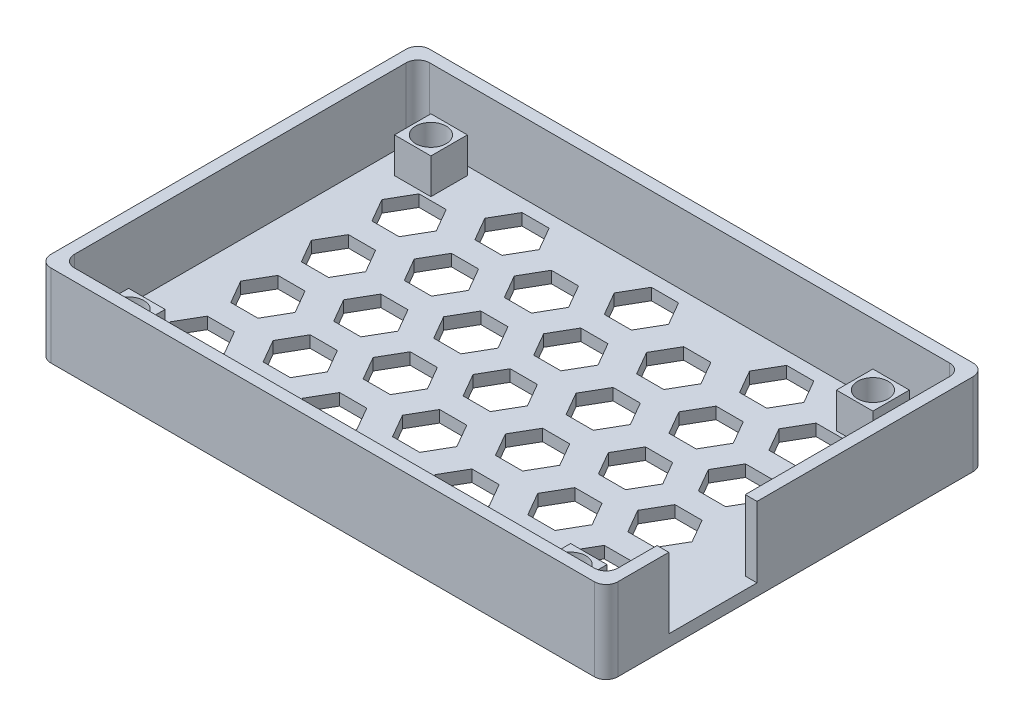
SolidWorks part; units mm, degrees
ref_plane "Plan de face" through (0, 0, 0) normal (0, 0, 1) x (1, 0, 0)
ref_plane "Plan de dessus" through (0, 0, 0) normal (0, 1, 0) x (1, 0, 0)
ref_plane "Plan de droite" through (0, 0, 0) normal (1, 0, 0) x (0, 0, -1)
sketch "Esquisse1" plane through (0, 0, 0) normal (0, 1, 0) x (1, 0, 0)
  line L1 (-48.6494, -29.5203) -> (47.3506, -29.5203)
  line L2 (-48.6494, -29.5203) -> (-48.6494, 34.4797)
  line L3 (-48.6494, 34.4797) -> (47.3506, 34.4797)
  line L4 (47.3506, -29.5203) -> (47.3506, 34.4797)
  dimension "D1" = 64
  dimension "D2" = 96
extrude "Boss.-Extru.1" add sketch "Esquisse1" along normal blind 14
sketch "Esquisse2" plane through (0, 14, 0) normal (0, 1, 0) x (1, 0, 0)
  line L0 (-48.6494, 34.4797) -> (-48.6494, -29.5203) construction
  line L1 (-46.6494, 32.4797) -> (45.3506, 32.4797)
  line L2 (-46.6494, 32.4797) -> (-46.6494, -27.5203)
  line L3 (-46.6494, -27.5203) -> (45.3506, -27.5203)
  line L4 (45.3506, 32.4797) -> (45.3506, -27.5203)
  line L5 (47.3506, 34.4797) -> (-48.6494, 34.4797) construction
  dimension "D1" = 2
  dimension "D2" = 92
  dimension "D3" = 2
  dimension "D4" = 60
extrude "Enlèv. mat.-Extru.1" cut sketch "Esquisse2" against normal blind 10.8
sketch "Esquisse3" plane through (0, 3.2, 0) normal (0, 1, 0) x (1, 0, 0)
  line L0 (45.3506, 32.4797) -> (-46.6494, 32.4797) construction
  line L1 (-37.6494, 32.4797) -> (30.3506, 32.4797)
  line L2 (-37.6494, 32.4797) -> (-37.6494, -27.5203)
  line L3 (-37.6494, -27.5203) -> (30.3506, -27.5203)
  line L4 (30.3506, 32.4797) -> (30.3506, -27.5203)
  line L5 (-46.6494, -27.5203) -> (45.3506, -27.5203) construction
  line L6 (-46.6494, 32.4797) -> (-46.6494, -27.5203) construction
  line L7 (45.3506, -27.5203) -> (45.3506, 32.4797) construction
  dimension "D1" = 9
  dimension "D2" = 15
extrude "Enlèv. mat.-Extru.2" cut sketch "Esquisse3" against normal blind 1.2
sketch "Esquisse4" plane through (0, 3.2, 0) normal (0, 1, 0) x (1, 0, 0)
  line L0 (-46.6494, 32.4797) -> (-46.6494, -27.5203) construction
  line L1 (-46.6494, 25.4797) -> (45.3506, 25.4797)
  line L2 (-46.6494, 25.4797) -> (-46.6494, -20.5203)
  line L3 (-46.6494, -20.5203) -> (45.3506, -20.5203)
  line L4 (45.3506, 25.4797) -> (45.3506, -20.5203)
  line L5 (45.3506, -27.5203) -> (45.3506, 32.4797) construction
  line L6 (-37.6494, 32.4797) -> (-46.6494, 32.4797) construction
  line L7 (-37.6494, -27.5203) -> (30.3506, -27.5203) construction
  dimension "D1" = 7
  dimension "D2" = 7
extrude "Enlèv. mat.-Extru.3" cut sketch "Esquisse4" against normal blind 1.2
sketch "Esquisse6" plane through (0, 3.2, 0) normal (0, 1, 0) x (1, 0, 0)
  line L0 (45.3506, 25.4797) -> (45.3506, 32.4797) construction
  line L1 (45.3506, -27.5203) -> (45.3506, -20.5203) construction
  line L2 (45.3506, 32.4797) -> (30.3506, 32.4797) construction
  line L4 (-37.6494, 32.4797) -> (-46.6494, 32.4797) construction
  circle A0 centre (-40.1294, 28.1747) radius 1.15
  circle A1 centre (-40.1294, -23.2153) radius 1.15
  circle A2 centre (35.0106, 28.1747) radius 1.15
  circle A3 centre (35.0106, -23.2153) radius 1.15
  dimension "D1" = 51.39
  dimension "D2" = 51.39
  dimension "D3" = 10.34
  dimension "D4" = 10.34
  dimension "D5" = 4.305
  dimension "D6" = 75.14
  dimension "D7" = 75.14
  dimension "D8" = 4.305
extrude "Boss.-Extru.2" add sketch "Esquisse6" along normal blind 4.8
sketch "Esquisse7" plane through (0, 3.2, 0) normal (0, 1, 0) x (1, 0, 0)
  line L1 (-42.2794, 30.3247) -> (-37.9794, 30.3247)
  line L2 (-42.2794, 30.3247) -> (-42.2794, 26.0247)
  line L3 (-42.2794, 26.0247) -> (-37.9794, 26.0247)
  line L4 (-37.9794, 30.3247) -> (-37.9794, 26.0247)
  line L5 (-42.2794, -25.3653) -> (-37.9794, -25.3653)
  line L6 (-42.2794, -25.3653) -> (-42.2794, -21.0653)
  line L7 (-42.2794, -21.0653) -> (-37.9794, -21.0653)
  line L8 (-37.9794, -25.3653) -> (-37.9794, -21.0653)
  line L9 (32.8606, 30.3247) -> (37.1606, 30.3247)
  line L10 (32.8606, 30.3247) -> (32.8606, 26.0247)
  line L11 (32.8606, 26.0247) -> (37.1606, 26.0247)
  line L12 (37.1606, 30.3247) -> (37.1606, 26.0247)
  line L13 (32.8606, -21.0653) -> (37.1606, -21.0653)
  line L14 (32.8606, -21.0653) -> (32.8606, -25.3653)
  line L15 (32.8606, -25.3653) -> (37.1606, -25.3653)
  line L16 (37.1606, -21.0653) -> (37.1606, -25.3653)
  circle A0 centre (-40.1294, 28.1747) radius 1.15
  circle A1 centre (-40.1294, -23.2153) radius 1.15
  circle A2 centre (35.0106, 28.1747) radius 1.15
  circle A3 centre (35.0106, -23.2153) radius 1.15
  dimension "D1" = 4.3
  dimension "D2" = 4.3
  dimension "D3" = 2.15
  dimension "D4" = 2.15
  dimension "D5" = 4.3
  dimension "D6" = 4.3
  dimension "D7" = 2.15
  dimension "D8" = 2.15
  dimension "D9" = 4.3
  dimension "D10" = 4.3
  dimension "D11" = 2.15
  dimension "D12" = 2.15
  dimension "D13" = 4.3
  dimension "D14" = 4.3
  dimension "D15" = 2.15
  dimension "D16" = 2.15
extrude "Boss.-Extru.3" add sketch "Esquisse7" along normal blind 4.8
sketch "Esquisse8" plane through (0, 8, 0) normal (0, 1, 0) x (1, 0, 0)
  line L0 (-37.9794, 30.3247) -> (-42.2794, 30.3247) construction
  line L1 (-42.2794, 30.3247) -> (-42.2794, 26.0247) construction
  line L2 (-42.2794, -21.0653) -> (-42.2794, -25.3653) construction
  line L3 (-37.9794, -21.0653) -> (-42.2794, -21.0653) construction
  line L4 (37.1606, -25.3653) -> (37.1606, -21.0653) construction
  line L5 (37.1606, -21.0653) -> (32.8606, -21.0653) construction
  line L6 (37.1606, 30.3247) -> (32.8606, 30.3247) construction
  line L7 (37.1606, 26.0247) -> (37.1606, 30.3247) construction
  circle A0 centre (-40.1294, -23.2153) radius 1.2
  circle A1 centre (-40.1294, 28.1747) radius 1.2
  circle A2 centre (35.0106, 28.1747) radius 1.2
  circle A3 centre (35.0106, -23.2153) radius 1.2
  dimension "D1" = 2.15
  dimension "D2" = 2.15
  dimension "D3" = 2.15
  dimension "D4" = 2.15
  dimension "D5" = 2.15
  dimension "D6" = 2.15
  dimension "D7" = 2.15
  dimension "D8" = 2.15
extrude "Enlèv. mat.-Extru.4" cut sketch "Esquisse8" against normal blind 4.8
sketch "Esquisse10" plane through (0, 3.2, 0) normal (0, 1, 0) x (1, 0, 0)
  line L1 (-46.6494, 32.4797) -> (45.3506, 32.4797)
  line L2 (-46.6494, 32.4797) -> (-46.6494, -27.5203)
  line L3 (-46.6494, -27.5203) -> (45.3506, -27.5203)
  line L4 (45.3506, 32.4797) -> (45.3506, -27.5203)
extrude "Enlèv. mat.-Extru.5" cut sketch "Esquisse10" against normal blind 1.2
sketch "Esquisse11" plane through (0, 2, 0) normal (0, 1, 0) x (1, 0, 0)
  line L1 (-42.2794, 30.3247) -> (-37.9794, 30.3247)
  line L2 (-42.2794, 30.3247) -> (-42.2794, 26.0247)
  line L3 (-42.2794, 26.0247) -> (-37.9794, 26.0247)
  line L4 (-37.9794, 30.3247) -> (-37.9794, 26.0247)
extrude "Boss.-Extru.4" add sketch "Esquisse11" along normal blind 1.2
sketch "Esquisse12" plane through (0, 2, 0) normal (0, 1, 0) x (1, 0, 0)
  line L1 (-42.2794, -21.0653) -> (-37.9794, -21.0653)
  line L2 (-42.2794, -21.0653) -> (-42.2794, -25.3653)
  line L3 (-42.2794, -25.3653) -> (-37.9794, -25.3653)
  line L4 (-37.9794, -21.0653) -> (-37.9794, -25.3653)
extrude "Boss.-Extru.5" add sketch "Esquisse12" along normal blind 1.2
sketch "Esquisse15" plane through (0, 2, 0) normal (0, 1, 0) x (1, 0, 0)
  line L1 (32.8606, 30.3247) -> (37.1606, 30.3247)
  line L2 (32.8606, 30.3247) -> (32.8606, 26.0247)
  line L3 (32.8606, 26.0247) -> (37.1606, 26.0247)
  line L4 (37.1606, 30.3247) -> (37.1606, 26.0247)
extrude "Boss.-Extru.8" add sketch "Esquisse15" along normal blind 1.2
sketch "Esquisse16" plane through (0, 2, 0) normal (0, 1, 0) x (1, 0, 0)
  line L1 (32.8606, -25.3653) -> (37.1606, -25.3653)
  line L2 (32.8606, -25.3653) -> (32.8606, -21.0653)
  line L3 (32.8606, -21.0653) -> (37.1606, -21.0653)
  line L4 (37.1606, -25.3653) -> (37.1606, -21.0653)
extrude "Boss.-Extru.9" add sketch "Esquisse16" along normal blind 1.2
sketch "Esquisse20" plane through (45.3506, 0, 0) normal (-1, 0, 0) x (0, 0, 1)
  line L0 (27.5203, 2) -> (-32.4797, 2) construction
  line L1 (19.0653, 2) -> (9.0653, 2)
  line L2 (19.0653, 2) -> (19.0653, 14)
  line L3 (19.0653, 14) -> (9.0653, 14)
  line L4 (9.0653, 2) -> (9.0653, 14)
  line L5 (21.0653, 8) -> (21.0653, 2) construction
  dimension "D1" = 2
  dimension "D2" = 10
  dimension "D3" = 12
extrude "Enlèv. mat.-Extru.8" cut sketch "Esquisse20" against normal blind 4.2
sketch "Esquisse22" plane through (0, 2, 0) normal (0, 1, 0) x (1, 0, 0)
  line L0 (45.3506, 32.4797) -> (-46.6494, 32.4797) construction
  line L1 (1.9694, 2.4797) -> (-0.34, 6.4797)
  line L2 (-0.34, 6.4797) -> (-4.9588, 6.4797)
  line L3 (-4.9588, 6.4797) -> (-7.2682, 2.4797)
  line L4 (-7.2682, 2.4797) -> (-4.9588, -1.5203)
  line L5 (-4.9588, -1.5203) -> (-0.34, -1.5203)
  line L6 (-0.34, -1.5203) -> (1.9694, 2.4797)
  line L8 (-46.6494, 32.4797) -> (-46.6494, -27.5203) construction
  line L9 (24.9694, 2.4797) -> (22.66, 6.4797)
  line L10 (22.66, 6.4797) -> (18.0412, 6.4797)
  line L11 (18.0412, 6.4797) -> (15.7318, 2.4797)
  line L12 (15.7318, 2.4797) -> (18.0412, -1.5203)
  line L13 (18.0412, -1.5203) -> (22.66, -1.5203)
  line L14 (22.66, -1.5203) -> (24.9694, 2.4797)
  line L15 (24.9694, 14.4797) -> (22.66, 18.4797)
  line L16 (22.66, 18.4797) -> (18.0412, 18.4797)
  line L17 (18.0412, 18.4797) -> (15.7318, 14.4797)
  line L18 (15.7318, 14.4797) -> (18.0412, 10.4797)
  line L19 (18.0412, 10.4797) -> (22.66, 10.4797)
  line L20 (22.66, 10.4797) -> (24.9694, 14.4797)
  line L21 (24.9694, 26.4797) -> (22.66, 30.4797)
  line L22 (22.66, 30.4797) -> (18.0412, 30.4797)
  line L23 (18.0412, 30.4797) -> (15.7318, 26.4797)
  line L24 (15.7318, 26.4797) -> (18.0412, 22.4797)
  line L25 (18.0412, 22.4797) -> (22.66, 22.4797)
  line L26 (22.66, 22.4797) -> (24.9694, 26.4797)
  line L27 (1.9694, 14.4797) -> (-0.34, 18.4797)
  line L28 (-0.34, 18.4797) -> (-4.9588, 18.4797)
  line L29 (-4.9588, 18.4797) -> (-7.2682, 14.4797)
  line L30 (-7.2682, 14.4797) -> (-4.9588, 10.4797)
  line L31 (-4.9588, 10.4797) -> (-0.34, 10.4797)
  line L32 (-0.34, 10.4797) -> (1.9694, 14.4797)
  line L33 (1.9694, 26.4797) -> (-0.34, 30.4797)
  line L34 (-0.34, 30.4797) -> (-4.9588, 30.4797)
  line L35 (-4.9588, 30.4797) -> (-7.2682, 26.4797)
  line L36 (-7.2682, 26.4797) -> (-4.9588, 22.4797)
  line L37 (-4.9588, 22.4797) -> (-0.34, 22.4797)
  line L38 (-0.34, 22.4797) -> (1.9694, 26.4797)
  line L39 (1.9694, -9.5203) -> (-0.34, -5.5203)
  line L40 (-0.34, -5.5203) -> (-4.9588, -5.5203)
  line L41 (-4.9588, -5.5203) -> (-7.2682, -9.5203)
  line L42 (-7.2682, -9.5203) -> (-4.9588, -13.5203)
  line L43 (-4.9588, -13.5203) -> (-0.34, -13.5203)
  line L44 (-0.34, -13.5203) -> (1.9694, -9.5203)
  line L45 (24.9694, -9.5203) -> (22.66, -5.5203)
  line L46 (22.66, -5.5203) -> (18.0412, -5.5203)
  line L47 (18.0412, -5.5203) -> (15.7318, -9.5203)
  line L48 (15.7318, -9.5203) -> (18.0412, -13.5203)
  line L49 (18.0412, -13.5203) -> (22.66, -13.5203)
  line L50 (22.66, -13.5203) -> (24.9694, -9.5203)
  line L51 (1.9694, -21.5203) -> (-0.34, -17.5203)
  line L52 (-0.34, -17.5203) -> (-4.9588, -17.5203)
  line L53 (-4.9588, -17.5203) -> (-7.2682, -21.5203)
  line L54 (-7.2682, -21.5203) -> (-4.9588, -25.5203)
  line L55 (-4.9588, -25.5203) -> (-0.34, -25.5203)
  line L56 (-0.34, -25.5203) -> (1.9694, -21.5203)
  line L57 (24.9694, -21.5203) -> (22.66, -17.5203)
  line L58 (22.66, -17.5203) -> (18.0412, -17.5203)
  line L59 (18.0412, -17.5203) -> (15.7318, -21.5203)
  line L60 (15.7318, -21.5203) -> (18.0412, -25.5203)
  line L61 (18.0412, -25.5203) -> (22.66, -25.5203)
  line L62 (22.66, -25.5203) -> (24.9694, -21.5203)
  line L63 (-20.0306, 26.4797) -> (-22.34, 30.4797)
  line L64 (-22.34, 30.4797) -> (-26.9588, 30.4797)
  line L65 (-26.9588, 30.4797) -> (-29.2682, 26.4797)
  line L66 (-29.2682, 26.4797) -> (-26.9588, 22.4797)
  line L67 (-26.9588, 22.4797) -> (-22.34, 22.4797)
  line L68 (-22.34, 22.4797) -> (-20.0306, 26.4797)
  line L69 (-20.0306, 14.4797) -> (-22.34, 18.4797)
  line L70 (-22.34, 18.4797) -> (-26.9588, 18.4797)
  line L71 (-26.9588, 18.4797) -> (-29.2682, 14.4797)
  line L72 (-29.2682, 14.4797) -> (-26.9588, 10.4797)
  line L73 (-26.9588, 10.4797) -> (-22.34, 10.4797)
  line L74 (-22.34, 10.4797) -> (-20.0306, 14.4797)
  line L75 (-20.0306, 2.4797) -> (-22.34, 6.4797)
  line L76 (-22.34, 6.4797) -> (-26.9588, 6.4797)
  line L77 (-26.9588, 6.4797) -> (-29.2682, 2.4797)
  line L78 (-29.2682, 2.4797) -> (-26.9588, -1.5203)
  line L79 (-26.9588, -1.5203) -> (-22.34, -1.5203)
  line L80 (-22.34, -1.5203) -> (-20.0306, 2.4797)
  line L81 (-20.0306, -9.5203) -> (-22.34, -5.5203)
  line L82 (-22.34, -5.5203) -> (-26.9588, -5.5203)
  line L83 (-26.9588, -5.5203) -> (-29.2682, -9.5203)
  line L84 (-29.2682, -9.5203) -> (-26.9588, -13.5203)
  line L85 (-26.9588, -13.5203) -> (-22.34, -13.5203)
  line L86 (-22.34, -13.5203) -> (-20.0306, -9.5203)
  line L87 (-20.0306, -21.5203) -> (-22.34, -17.5203)
  line L88 (-22.34, -17.5203) -> (-26.9588, -17.5203)
  line L89 (-26.9588, -17.5203) -> (-29.2682, -21.5203)
  line L90 (-29.2682, -21.5203) -> (-26.9588, -25.5203)
  line L91 (-26.9588, -25.5203) -> (-22.34, -25.5203)
  line L92 (-22.34, -25.5203) -> (-20.0306, -21.5203)
  circle A0 centre (-2.6494, 2.4797) radius 4 construction
  dimension "D1" = 30
  dimension "D2" = 44
  dimension "D3" = 2
  dimension "D4" = 3
  dimension "D5" = 3
  dimension "D6" = 2
extrude "Enlèv. mat.-Extru.9" cut sketch "Esquisse22" against normal blind 4.2
sketch "Esquisse23" plane through (0, 2, 0) normal (0, 1, 0) x (1, 0, 0)
  line L0 (-4.9588, 10.4797) -> (-0.34, 10.4797) construction
  line L1 (-9.0306, 8.4797) -> (-11.34, 12.4797)
  line L2 (-11.34, 12.4797) -> (-15.9588, 12.4797)
  line L3 (-15.9588, 12.4797) -> (-18.2682, 8.4797)
  line L4 (-18.2682, 8.4797) -> (-15.9588, 4.4797)
  line L5 (-15.9588, 4.4797) -> (-11.34, 4.4797)
  line L6 (-11.34, 4.4797) -> (-9.0306, 8.4797)
  line L9 (-46.6494, 32.4797) -> (-46.6494, -27.5203) construction
  line L10 (13.4694, 8.4797) -> (11.16, 12.4797)
  line L11 (11.16, 12.4797) -> (6.5412, 12.4797)
  line L12 (6.5412, 12.4797) -> (4.2318, 8.4797)
  line L13 (4.2318, 8.4797) -> (6.5412, 4.4797)
  line L14 (6.5412, 4.4797) -> (11.16, 4.4797)
  line L15 (11.16, 4.4797) -> (13.4694, 8.4797)
  line L16 (13.4694, 20.4797) -> (11.16, 24.4797)
  line L17 (11.16, 24.4797) -> (6.5412, 24.4797)
  line L18 (6.5412, 24.4797) -> (4.2318, 20.4797)
  line L19 (4.2318, 20.4797) -> (6.5412, 16.4797)
  line L20 (6.5412, 16.4797) -> (11.16, 16.4797)
  line L21 (11.16, 16.4797) -> (13.4694, 20.4797)
  line L22 (-9.0306, 20.4797) -> (-11.34, 24.4797)
  line L23 (-11.34, 24.4797) -> (-15.9588, 24.4797)
  line L24 (-15.9588, 24.4797) -> (-18.2682, 20.4797)
  line L25 (-18.2682, 20.4797) -> (-15.9588, 16.4797)
  line L26 (-15.9588, 16.4797) -> (-11.34, 16.4797)
  line L27 (-11.34, 16.4797) -> (-9.0306, 20.4797)
  line L28 (-9.0306, -3.5203) -> (-11.34, 0.4797)
  line L29 (-11.34, 0.4797) -> (-15.9588, 0.4797)
  line L30 (-15.9588, 0.4797) -> (-18.2682, -3.5203)
  line L31 (-18.2682, -3.5203) -> (-15.9588, -7.5203)
  line L32 (-15.9588, -7.5203) -> (-11.34, -7.5203)
  line L33 (-11.34, -7.5203) -> (-9.0306, -3.5203)
  line L34 (13.4694, -3.5203) -> (11.16, 0.4797)
  line L35 (11.16, 0.4797) -> (6.5412, 0.4797)
  line L36 (6.5412, 0.4797) -> (4.2318, -3.5203)
  line L37 (4.2318, -3.5203) -> (6.5412, -7.5203)
  line L38 (6.5412, -7.5203) -> (11.16, -7.5203)
  line L39 (11.16, -7.5203) -> (13.4694, -3.5203)
  line L40 (-9.0306, -15.5203) -> (-11.34, -11.5203)
  line L41 (-11.34, -11.5203) -> (-15.9588, -11.5203)
  line L42 (-15.9588, -11.5203) -> (-18.2682, -15.5203)
  line L43 (-18.2682, -15.5203) -> (-15.9588, -19.5203)
  line L44 (-15.9588, -19.5203) -> (-11.34, -19.5203)
  line L45 (-11.34, -19.5203) -> (-9.0306, -15.5203)
  line L46 (13.4694, -15.5203) -> (11.16, -11.5203)
  line L47 (11.16, -11.5203) -> (6.5412, -11.5203)
  line L48 (6.5412, -11.5203) -> (4.2318, -15.5203)
  line L49 (4.2318, -15.5203) -> (6.5412, -19.5203)
  line L50 (6.5412, -19.5203) -> (11.16, -19.5203)
  line L51 (11.16, -19.5203) -> (13.4694, -15.5203)
  line L52 (35.9694, 8.4797) -> (33.66, 12.4797)
  line L53 (33.66, 12.4797) -> (29.0412, 12.4797)
  line L54 (29.0412, 12.4797) -> (26.7318, 8.4797)
  line L55 (26.7318, 8.4797) -> (29.0412, 4.4797)
  line L56 (29.0412, 4.4797) -> (33.66, 4.4797)
  line L57 (33.66, 4.4797) -> (35.9694, 8.4797)
  line L58 (35.9694, -3.5203) -> (33.66, 0.4797)
  line L59 (33.66, 0.4797) -> (29.0412, 0.4797)
  line L60 (29.0412, 0.4797) -> (26.7318, -3.5203)
  line L61 (26.7318, -3.5203) -> (29.0412, -7.5203)
  line L62 (29.0412, -7.5203) -> (33.66, -7.5203)
  line L63 (33.66, -7.5203) -> (35.9694, -3.5203)
  line L64 (35.9694, 20.4797) -> (33.66, 24.4797)
  line L65 (33.66, 24.4797) -> (29.0412, 24.4797)
  line L66 (29.0412, 24.4797) -> (26.7318, 20.4797)
  line L67 (26.7318, 20.4797) -> (29.0412, 16.4797)
  line L68 (29.0412, 16.4797) -> (33.66, 16.4797)
  line L69 (33.66, 16.4797) -> (35.9694, 20.4797)
  line L70 (35.9694, -15.5203) -> (33.66, -11.5203)
  line L71 (33.66, -11.5203) -> (29.0412, -11.5203)
  line L72 (29.0412, -11.5203) -> (26.7318, -15.5203)
  line L73 (26.7318, -15.5203) -> (29.0412, -19.5203)
  line L74 (29.0412, -19.5203) -> (33.66, -19.5203)
  line L75 (33.66, -19.5203) -> (35.9694, -15.5203)
  line L76 (-31.5306, 20.4797) -> (-33.84, 24.4797)
  line L77 (-33.84, 24.4797) -> (-38.4588, 24.4797)
  line L78 (-38.4588, 24.4797) -> (-40.7682, 20.4797)
  line L79 (-40.7682, 20.4797) -> (-38.4588, 16.4797)
  line L80 (-38.4588, 16.4797) -> (-33.84, 16.4797)
  line L81 (-33.84, 16.4797) -> (-31.5306, 20.4797)
  line L82 (-31.5306, 8.4797) -> (-33.84, 12.4797)
  line L83 (-33.84, 12.4797) -> (-38.4588, 12.4797)
  line L84 (-38.4588, 12.4797) -> (-40.7682, 8.4797)
  line L85 (-40.7682, 8.4797) -> (-38.4588, 4.4797)
  line L86 (-38.4588, 4.4797) -> (-33.84, 4.4797)
  line L87 (-33.84, 4.4797) -> (-31.5306, 8.4797)
  line L88 (-31.5306, -3.5203) -> (-33.84, 0.4797)
  line L89 (-33.84, 0.4797) -> (-38.4588, 0.4797)
  line L90 (-38.4588, 0.4797) -> (-40.7682, -3.5203)
  line L91 (-40.7682, -3.5203) -> (-38.4588, -7.5203)
  line L92 (-38.4588, -7.5203) -> (-33.84, -7.5203)
  line L93 (-33.84, -7.5203) -> (-31.5306, -3.5203)
  line L94 (-31.5306, -15.5203) -> (-33.84, -11.5203)
  line L95 (-33.84, -11.5203) -> (-38.4588, -11.5203)
  line L96 (-38.4588, -11.5203) -> (-40.7682, -15.5203)
  line L97 (-40.7682, -15.5203) -> (-38.4588, -19.5203)
  line L98 (-38.4588, -19.5203) -> (-33.84, -19.5203)
  line L99 (-33.84, -19.5203) -> (-31.5306, -15.5203)
  circle A0 centre (-13.6494, 8.4797) radius 4 construction
  dimension "D1" = 2
  dimension "D2" = 33
  dimension "D3" = 2
  dimension "D4" = 2
  dimension "D5" = 3
  dimension "D6" = 2
  dimension "D7" = 2
extrude "Enlèv. mat.-Extru.10" cut sketch "Esquisse23" against normal blind 4.2
sketch "Esquisse25" plane through (0, 0, 27.5203) normal (0, 0, -1) x (-1, 0, 0)
  line L1 (-45.3506, 14) -> (46.6494, 14)
  line L2 (-45.3506, 14) -> (-45.3506, 2)
  line L3 (-45.3506, 2) -> (46.6494, 2)
  line L4 (46.6494, 14) -> (46.6494, 2)
extrude "Enlèv. mat.-Extru.11" cut sketch "Esquisse25" against normal blind 0.2
sketch "Esquisse26" plane through (0, 0, -32.4797) normal (0, 0, 1) x (1, 0, 0)
  line L1 (-46.6494, 14) -> (45.3506, 14)
  line L2 (-46.6494, 14) -> (-46.6494, 2)
  line L3 (-46.6494, 2) -> (45.3506, 2)
  line L4 (45.3506, 14) -> (45.3506, 2)
extrude "Enlèv. mat.-Extru.12" cut sketch "Esquisse26" against normal blind 0.2
sketch "Esquisse27" plane through (-46.6494, 0, 0) normal (1, 0, 0) x (0, 0, -1)
  line L1 (-27.7203, 14) -> (32.6797, 14)
  line L2 (-27.7203, 14) -> (-27.7203, 2)
  line L3 (-27.7203, 2) -> (32.6797, 2)
  line L4 (32.6797, 14) -> (32.6797, 2)
extrude "Enlèv. mat.-Extru.13" cut sketch "Esquisse27" against normal blind 0.2
sketch "Esquisse29" plane through (45.3506, 0, 0) normal (-1, 0, 0) x (0, 0, 1)
  line L1 (-32.6797, 14) -> (27.7203, 14)
  line L2 (-32.6797, 14) -> (-32.6797, 2)
  line L3 (-32.6797, 2) -> (27.7203, 2)
  line L4 (27.7203, 14) -> (27.7203, 2)
extrude "Enlèv. mat.-Extru.14" cut sketch "Esquisse29" against normal blind 0.2
sketch "Esquisse30" plane through (0, 0, -34.4797) normal (0, 0, -1) x (-1, 0, 0)
  line L1 (-47.3506, 0) -> (48.6494, 0)
  line L2 (-47.3506, 0) -> (-47.3506, 14)
  line L3 (-47.3506, 14) -> (48.6494, 14)
  line L4 (48.6494, 0) -> (48.6494, 14)
extrude "Boss.-Extru.10" add sketch "Esquisse30" along normal blind 0.2
sketch "Esquisse31" plane through (0, 0, 29.5203) normal (0, 0, 1) x (1, 0, 0)
  line L1 (-48.6494, 14) -> (47.3506, 14)
  line L2 (-48.6494, 14) -> (-48.6494, 0)
  line L3 (-48.6494, 0) -> (47.3506, 0)
  line L4 (47.3506, 14) -> (47.3506, 0)
extrude "Boss.-Extru.11" add sketch "Esquisse31" along normal blind 0.2
sketch "Esquisse32" plane through (-48.6494, 0, 0) normal (-1, 0, 0) x (0, 0, 1)
  line L1 (-34.6797, 14) -> (29.7203, 14)
  line L2 (-34.6797, 14) -> (-34.6797, 0)
  line L3 (-34.6797, 0) -> (29.7203, 0)
  line L4 (29.7203, 14) -> (29.7203, 0)
extrude "Boss.-Extru.12" add sketch "Esquisse32" along normal blind 0.2
sketch "Esquisse36" plane through (47.3506, 0, 0) normal (1, 0, 0) x (0, 0, -1)
  line L0 (-19.0653, 14) -> (-29.7203, 14)
  line L1 (-29.7203, 14) -> (-29.7203, 0)
  line L2 (-29.7203, 0) -> (34.6797, 0)
  line L3 (34.6797, 0) -> (34.6797, 14)
  line L4 (34.6797, 14) -> (-9.0653, 14)
  line L5 (-9.0653, 14) -> (-9.0653, 2)
  line L6 (-9.0653, 2) -> (-19.0653, 2)
  line L7 (-19.0653, 2) -> (-19.0653, 14)
extrude "Boss.-Extru.15" add sketch "Esquisse36" along normal blind 0.2
fillet "Congé1" radius 2 8 edges at (45.5506, 8, -32.6797) (-46.8494, 8, -32.6797) (-46.8494, 8, 27.7203) (45.5506, 8, 27.7203) (47.5506, 7, 29.7203) (-48.8494, 7, 29.7203) (-48.8494, 7, -34.6797) (47.5506, 7, -34.6797)
sketch "Esquisse37" plane through (0, 0, 9.0653) normal (0, 0, 1) x (1, 0, 0)
  line L1 (45.5506, 2) -> (47.5506, 2)
  line L2 (45.5506, 2) -> (45.5506, 14)
  line L3 (45.5506, 14) -> (47.5506, 14)
  line L4 (47.5506, 2) -> (47.5506, 14)
extrude "Enlèv. mat.-Extru.15" cut sketch "Esquisse37" against normal blind 5
sketch "Esquisse38" plane through (0, 8, 0) normal (0, 1, 0) x (1, 0, 0)
  line L0 (-42.2794, -21.0653) -> (-42.2794, -25.3653) construction
  line L1 (-43.2294, -20.1153) -> (-37.0294, -20.1153)
  line L2 (-43.2294, -20.1153) -> (-43.2294, -26.3153)
  line L3 (-43.2294, -26.3153) -> (-37.0294, -26.3153)
  line L4 (-37.0294, -20.1153) -> (-37.0294, -26.3153)
  line L5 (-37.9794, -21.0653) -> (-42.2794, -21.0653) construction
  dimension "D1" = 6.2
  dimension "D2" = 6.2
  dimension "D3" = 0.95
  dimension "D4" = 0.95
extrude "Boss.-Extru.16" add sketch "Esquisse38" against normal blind 7
sketch "Esquisse41" plane through (0, 8, 0) normal (0, 1, 0) x (1, 0, 0)
  line L0 (-37.0294, -20.1153) -> (-43.2294, -20.1153) construction
  line L1 (-37.0294, -26.3153) -> (-37.0294, -20.1153) construction
  circle A0 centre (-40.1294, -23.2153) radius 2.6
  dimension "D1" = 3.1
  dimension "D2" = 3.1
extrude "Enlèv. mat.-Extru.16" cut sketch "Esquisse41" against normal blind 6
sketch "Esquisse42" plane through (0, 8, 0) normal (0, 1, 0) x (1, 0, 0)
  line L0 (-37.9794, 30.3247) -> (-42.2794, 30.3247) construction
  line L1 (-43.2294, 31.2747) -> (-37.0294, 31.2747)
  line L2 (-43.2294, 31.2747) -> (-43.2294, 25.0747)
  line L3 (-43.2294, 25.0747) -> (-37.0294, 25.0747)
  line L4 (-37.0294, 31.2747) -> (-37.0294, 25.0747)
  line L5 (-37.9794, 26.0247) -> (-37.9794, 30.3247) construction
  dimension "D1" = 6.2
  dimension "D2" = 6.2
  dimension "D3" = 0.95
  dimension "D4" = 0.95
extrude "Boss.-Extru.17" add sketch "Esquisse42" against normal blind 6
sketch "Esquisse43" plane through (0, 8, 0) normal (0, 1, 0) x (1, 0, 0)
  line L0 (32.8606, 30.3247) -> (32.8606, 26.0247) construction
  line L1 (31.9106, 31.2747) -> (38.1106, 31.2747)
  line L2 (31.9106, 31.2747) -> (31.9106, 25.0747)
  line L3 (31.9106, 25.0747) -> (38.1106, 25.0747)
  line L4 (38.1106, 31.2747) -> (38.1106, 25.0747)
  line L5 (38.1106, -20.1153) -> (31.9106, -20.1153)
  line L6 (38.1106, -20.1153) -> (38.1106, -26.3153)
  line L7 (38.1106, -26.3153) -> (31.9106, -26.3153)
  line L8 (31.9106, -20.1153) -> (31.9106, -26.3153)
  line L10 (32.8606, 26.0247) -> (37.1606, 26.0247) construction
  line L11 (32.8606, -21.0653) -> (32.8606, -25.3653) construction
  line L12 (37.1606, -21.0653) -> (32.8606, -21.0653) construction
  point P14 (32.8606, -23.2153)
  dimension "D1" = 6.2
  dimension "D2" = 6.2
  dimension "D3" = 0.95
  dimension "D4" = 0.95
  dimension "D5" = 6.2
  dimension "D6" = 6.2
  dimension "D7" = 0.95
  dimension "D8" = 0.95
extrude "Boss.-Extru.18" add sketch "Esquisse43" against normal blind 6
sketch "Esquisse44" plane through (0, 8, 0) normal (0, 1, 0) x (1, 0, 0)
  line L0 (-43.2294, 25.0747) -> (-37.0294, 25.0747) construction
  line L1 (-37.0294, 25.0747) -> (-37.0294, 31.2747) construction
  line L2 (38.1106, 25.0747) -> (38.1106, 31.2747) construction
  line L3 (31.9106, 25.0747) -> (38.1106, 25.0747) construction
  line L4 (38.1106, -26.3153) -> (38.1106, -20.1153) construction
  line L5 (38.1106, -20.1153) -> (31.9106, -20.1153) construction
  circle A0 centre (-40.1294, 28.1747) radius 2.6
  circle A1 centre (35.0106, 28.1747) radius 2.6
  circle A2 centre (35.0106, -23.2153) radius 2.6
  point P12 (38.1106, 28.1747)
  dimension "D1" = 3.1
  dimension "D2" = 3.1
  dimension "D3" = 3.1
  dimension "D4" = 3.1
  dimension "D5" = 3.1
  dimension "D6" = 3.1
extrude "Enlèv. mat.-Extru.17" cut sketch "Esquisse44" against normal blind 6
